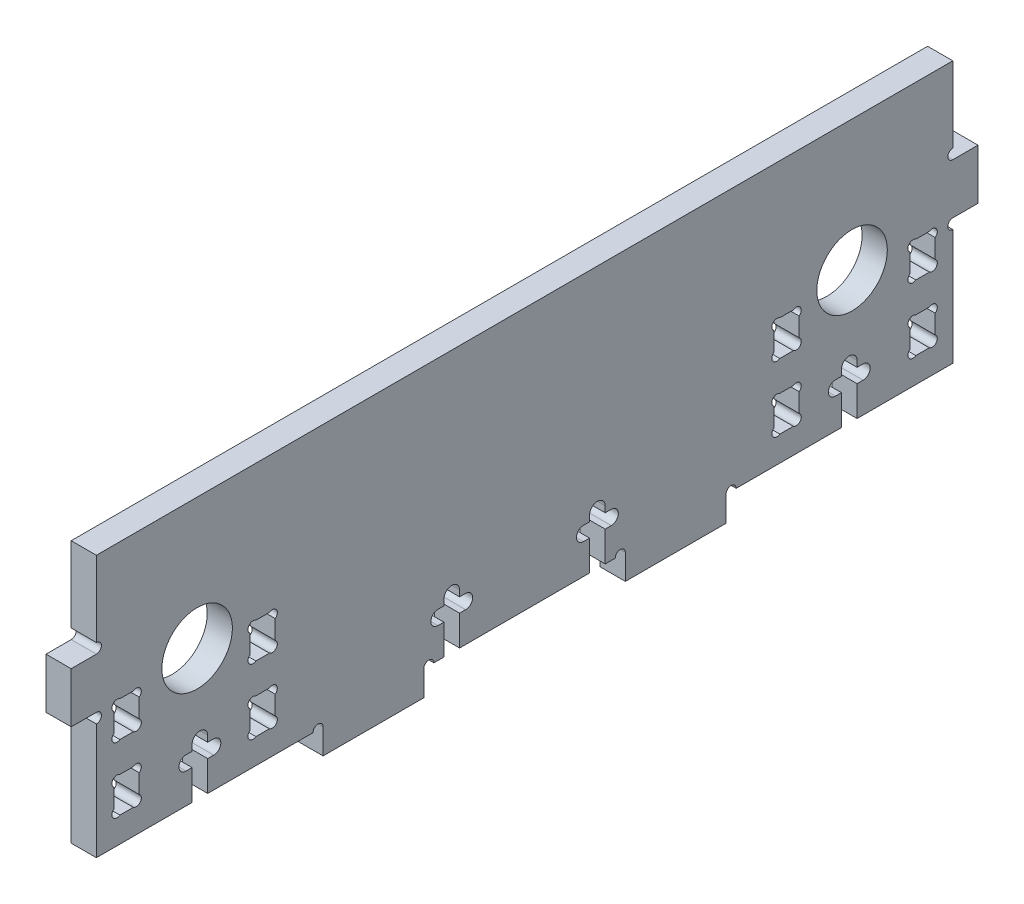
SolidWorks part; units mm, degrees
ref_plane "정면" through (0, 0, 0) normal (0, 0, 1) x (1, 0, 0)
ref_plane "윗면" through (0, 0, 0) normal (0, 1, 0) x (1, 0, 0)
ref_plane "우측면" through (0, 0, 0) normal (1, 0, 0) x (0, 0, -1)
sketch "스케치1" plane through (0, 0, 0) normal (1, 0, 0) x (0, 0, -1)
  line L1 (0, 0) -> (170, 0)
  line L2 (0, 0) -> (0, 52)
  line L3 (0, 52) -> (170, 52)
  line L4 (170, 0) -> (170, 52)
  dimension "D1" = 170
  dimension "D2" = 52
extrude "보스-돌출1" add sketch "스케치1" along normal blind 5
sketch "스케치2" plane through (5, 0, 0) normal (1, 0, 0) x (0, 0, -1)
  line L0 (170, 26) -> (150, 26) construction
  line L1 (170, 0) -> (170, 52) construction
  line L2 (150, 26) -> (20, 26) construction
  line L3 (20, 26) -> (0, 26) construction
  line L4 (0, 52) -> (0, 0) construction
  circle A0 centre (150, 26) radius 7
  circle A1 centre (20, 26) radius 7
  dimension "D2" = 14
  dimension "D1" = 20
extrude "컷-돌출1" cut sketch "스케치2" against normal blind 10
sketch "스케치3" plane through (5, 0, 0) normal (1, 0, 0) x (0, 0, -1)
  line L0 (0, 0) -> (170, 0) construction
  line L1 (45, 0) -> (65, 0)
  line L2 (45, 0) -> (45, -5)
  line L3 (45, -5) -> (65, -5)
  line L4 (65, 0) -> (65, -5)
  line L5 (0, -5) -> (45, -5) construction
  line L6 (65, -5) -> (105, -5) construction
  line L7 (125, 0) -> (105, 0)
  line L8 (125, 0) -> (125, -5)
  line L9 (125, -5) -> (105, -5)
  line L10 (105, 0) -> (105, -5)
  line L11 (125, -5) -> (170, -5) construction
  line L12 (170, -5) -> (170, 0) construction
  line L13 (0, 0) -> (0, -5) construction
  line L14 (0, 0) -> (0, -5) construction
  line L15 (0, -5) -> (45, -5) construction
  dimension "D1" = 45
  dimension "D2" = 20
extrude "보스-돌출2" add sketch "스케치3" against normal blind 5
sketch "스케치6" plane through (5, 0, 0) normal (1, 0, 0) x (0, 0, -1)
  line L0 (151, 0) -> (151, 6)
  line L1 (147.9, 10) -> (151, 10) construction
  line L2 (146.7, 6) -> (146.7, 8.8) construction
  line L3 (151, 6) -> (151, 8.8) construction
  line L4 (147.9, 0) -> (151, 0)
  line L5 (146.7, 8.8) -> (147.9, 8.8)
  line L6 (147.9, 0) -> (147.9, 6)
  line L7 (152.2, 8.8) -> (152.2, 6) construction
  line L8 (147.9, 6) -> (146.7, 6)
  line L9 (147.9, 8.8) -> (147.9, 6) construction
  line L10 (151, 8.8) -> (151, 10)
  line L11 (147.9, 6) -> (151, 6) construction
  line L12 (147.9, 8.8) -> (151, 8.8) construction
  line L13 (151, 8.8) -> (152.2, 8.8)
  line L14 (147.9, 8.8) -> (147.9, 10)
  line L15 (149.45, 10) -> (149.45, 12.1831) construction
  line L16 (152.2, 6) -> (151, 6)
  line L18 (65, 0) -> (105, 0) construction
  line L19 (101, 0) -> (101, 6)
  line L20 (97.9, 10) -> (101, 10) construction
  line L21 (96.7, 6) -> (96.7, 8.8) construction
  line L22 (101, 6) -> (101, 8.8) construction
  line L23 (97.9, 0) -> (101, 0)
  line L24 (96.7, 8.8) -> (97.9, 8.8)
  line L25 (97.9, 0) -> (97.9, 6)
  line L26 (102.2, 8.8) -> (102.2, 6) construction
  line L27 (97.9, 6) -> (96.7, 6)
  line L28 (97.9, 8.8) -> (97.9, 6) construction
  line L29 (101, 8.8) -> (101, 10)
  line L30 (97.9, 6) -> (101, 6) construction
  line L31 (97.9, 8.8) -> (101, 8.8) construction
  line L32 (101, 8.8) -> (102.2, 8.8)
  line L33 (97.9, 8.8) -> (97.9, 10)
  line L34 (99.45, 10) -> (99.45, 12.1831) construction
  line L35 (102.2, 6) -> (101, 6)
  line L37 (105, 0) -> (105, -5) construction
  line L71 (85, 52) -> (85, 0) construction
  line L72 (170, 52) -> (0, 52) construction
  line L89 (70.55, 10) -> (70.55, 12.1831) construction
  line L90 (72.1, 8.8) -> (69, 8.8) construction
  line L91 (72.1, 6) -> (69, 6) construction
  line L92 (72.1, 8.8) -> (72.1, 6) construction
  line L93 (67.8, 8.8) -> (67.8, 6) construction
  line L94 (69, 6) -> (69, 8.8) construction
  line L95 (73.3, 6) -> (73.3, 8.8) construction
  line L96 (72.1, 10) -> (69, 10) construction
  line L97 (20.55, 10) -> (20.55, 12.1831) construction
  line L98 (22.1, 8.8) -> (19, 8.8) construction
  line L99 (22.1, 6) -> (19, 6) construction
  line L100 (22.1, 8.8) -> (22.1, 6) construction
  line L101 (17.8, 8.8) -> (17.8, 6) construction
  line L102 (19, 6) -> (19, 8.8) construction
  line L103 (23.3, 6) -> (23.3, 8.8) construction
  line L104 (22.1, 10) -> (19, 10) construction
  line L123 (67.8, 6) -> (69, 6)
  line L124 (72.1, 8.8) -> (72.1, 10)
  line L125 (69, 8.8) -> (67.8, 8.8)
  line L126 (69, 8.8) -> (69, 10)
  line L127 (72.1, 6) -> (73.3, 6)
  line L128 (72.1, 0) -> (72.1, 6)
  line L129 (73.3, 8.8) -> (72.1, 8.8)
  line L130 (72.1, 0) -> (69, 0)
  line L131 (69, 0) -> (69, 6)
  line L132 (17.8, 6) -> (19, 6)
  line L133 (22.1, 8.8) -> (22.1, 10)
  line L134 (19, 8.8) -> (17.8, 8.8)
  line L135 (19, 8.8) -> (19, 10)
  line L136 (22.1, 6) -> (23.3, 6)
  line L137 (22.1, 0) -> (22.1, 6)
  line L138 (23.3, 8.8) -> (22.1, 8.8)
  line L139 (22.1, 0) -> (19, 0)
  line L140 (19, 0) -> (19, 6)
  arc A0 (151, 10) -> (147.9, 10) centre (149.45, 10) ccw
  arc A1 (146.7, 8.8) -> (146.7, 6) centre (146.7, 7.4) ccw
  arc A2 (152.2, 6) -> (152.2, 8.8) centre (152.2, 7.4) ccw
  arc A3 (101, 10) -> (97.9, 10) centre (99.45, 10) ccw
  arc A4 (96.7, 8.8) -> (96.7, 6) centre (96.7, 7.4) ccw
  arc A5 (102.2, 6) -> (102.2, 8.8) centre (102.2, 7.4) ccw
  arc A18 (67.8, 6) -> (67.8, 8.8) centre (67.8, 7.4) cw
  arc A19 (73.3, 8.8) -> (73.3, 6) centre (73.3, 7.4) cw
  arc A20 (69, 10) -> (72.1, 10) centre (70.55, 10) cw
  arc A21 (17.8, 6) -> (17.8, 8.8) centre (17.8, 7.4) cw
  arc A22 (23.3, 8.8) -> (23.3, 6) centre (23.3, 7.4) cw
  arc A23 (19, 10) -> (22.1, 10) centre (20.55, 10) cw
  dimension "D1" = 3.1
  dimension "D2" = 4
  dimension "D3" = 5.5
  dimension "D4" = 2.8
  dimension "D7" = 3.1
  dimension "D9" = 5.5
  dimension "D10" = 2.8
  dimension "D12" = 50
extrude "컷-돌출2" cut sketch "스케치6" against normal blind 10
sketch "스케치8" plane through (5, 0, 0) normal (1, 0, 0) x (0, 0, -1)
  line L0 (170, 0) -> (170, 52) construction
  line L1 (170, 35) -> (175, 35)
  line L2 (170, 35) -> (170, 25)
  line L3 (170, 25) -> (175, 25)
  line L4 (175, 35) -> (175, 25)
  line L5 (175, 52) -> (175, 35) construction
  line L8 (85, 0) -> (85, 52) construction
  line L9 (72.1, 0) -> (97.9, 0) construction
  line L10 (170, 52) -> (0, 52) construction
  line L11 (-5, 35) -> (-5, 25)
  line L12 (0, 25) -> (-5, 25)
  line L13 (0, 35) -> (0, 25)
  line L14 (0, 35) -> (-5, 35)
  line L15 (151, 0) -> (170, 0) construction
  dimension "D1" = 25
  dimension "D2" = 10
extrude "보스-돌출3" add sketch "스케치8" against normal blind 5
sketch "스케치7" plane through (5, 0, 0) normal (1, 0, 0) x (0, 0, -1)
  line L0 (65, 0) -> (69, 0) construction
  line L1 (22.1, 0) -> (45, 0) construction
  line L2 (101, 0) -> (105, 0) construction
  line L3 (125, 0) -> (147.9, 0) construction
  line L4 (170, 35) -> (170, 52) construction
  line L5 (170, 0) -> (170, 25) construction
  line L6 (0, 52) -> (0, 35) construction
  line L7 (0, 25) -> (0, 0) construction
  circle A0 centre (66, 0) radius 1
  circle A1 centre (44, 0) radius 1
  circle A2 centre (104, 0) radius 1
  circle A3 centre (126, 0) radius 1
  circle A4 centre (170, 36) radius 1
  circle A5 centre (170, 24) radius 1
  circle A6 centre (0, 36) radius 1
  circle A7 centre (0, 24) radius 1
  dimension "D1" = 2
extrude "컷-돌출3" cut sketch "스케치7" against normal blind 10
sketch "스케치10" plane through (0, 0, 0) normal (-1, 0, 0) x (0, 0, 1)
  line L0 (-166.5, 25) -> (-161.5, 18) construction
  line L1 (-166.5, 18) -> (-161.5, 18)
  line L2 (-166.5, 18) -> (-166.5, 25)
  line L3 (-166.5, 25) -> (-161.5, 25)
  line L4 (-161.5, 18) -> (-161.5, 25)
  line L5 (-161.5, 25) -> (-166.5, 18) construction
  line L6 (-85, 52) -> (-85, 0) construction
  line L7 (-139.5, 18) -> (-134.5, 18)
  line L8 (-139.5, 18) -> (-139.5, 25)
  line L9 (-139.5, 25) -> (-134.5, 25)
  line L10 (-134.5, 18) -> (-134.5, 25)
  line L11 (-166.5, 5) -> (-161.5, 5)
  line L12 (-166.5, 5) -> (-166.5, 12)
  line L13 (-166.5, 12) -> (-161.5, 12)
  line L14 (-161.5, 5) -> (-161.5, 12)
  line L15 (-139.5, 12) -> (-134.5, 12)
  line L16 (-139.5, 12) -> (-139.5, 5)
  line L17 (-139.5, 5) -> (-134.5, 5)
  line L18 (-134.5, 12) -> (-134.5, 5)
  line L19 (-170, 52) -> (0, 52) construction
  line L20 (-72.1, 0) -> (-97.9, 0) construction
  line L21 (-8.5, 25) -> (-3.5, 18) construction
  line L22 (-3.5, 25) -> (-8.5, 18) construction
  line L23 (-35.5, 12) -> (-35.5, 5)
  line L24 (-30.5, 5) -> (-35.5, 5)
  line L25 (-30.5, 12) -> (-30.5, 5)
  line L26 (-30.5, 12) -> (-35.5, 12)
  line L27 (-8.5, 5) -> (-8.5, 12)
  line L28 (-3.5, 12) -> (-8.5, 12)
  line L29 (-3.5, 5) -> (-3.5, 12)
  line L30 (-3.5, 5) -> (-8.5, 5)
  line L31 (-35.5, 18) -> (-35.5, 25)
  line L32 (-30.5, 25) -> (-35.5, 25)
  line L33 (-30.5, 18) -> (-30.5, 25)
  line L34 (-30.5, 18) -> (-35.5, 18)
  line L35 (-8.5, 18) -> (-8.5, 25)
  line L36 (-3.5, 25) -> (-8.5, 25)
  line L37 (-3.5, 18) -> (-3.5, 25)
  line L38 (-3.5, 18) -> (-8.5, 18)
extrude "컷-돌출4" cut sketch "스케치10" against normal blind 10
sketch "스케치11" plane through (5, 0, 0) normal (1, 0, 0) x (0, 0, -1)
  line L0 (85, 52) -> (85, 0) construction
  line L1 (170, 52) -> (0, 52) construction
  line L2 (72.1, 0) -> (97.9, 0) construction
  line L3 (161.5, 25) -> (166.5, 18) construction
  line L4 (166.5, 25) -> (161.5, 18) construction
  line L5 (139.5, 18) -> (161.5, 18) construction
  line L6 (161.5, 18) -> (161.5, 12) construction
  line L7 (161.5, 12) -> (139.5, 12) construction
  line L8 (139.5, 12) -> (139.5, 18) construction
  line L9 (150.5, 18) -> (150.5, 12) construction
  line L10 (139.5, 15) -> (161.5, 15) construction
  line L11 (134.5, 25) -> (139.5, 18) construction
  line L12 (139.5, 25) -> (134.5, 18) construction
  line L13 (139.5, 5) -> (134.5, 12) construction
  line L14 (134.5, 5) -> (139.5, 12) construction
  line L15 (166.5, 5) -> (161.5, 12) construction
  line L16 (161.5, 5) -> (166.5, 12) construction
  line L17 (8.5, 5) -> (3.5, 12) construction
  line L18 (3.5, 5) -> (8.5, 12) construction
  line L19 (35.5, 5) -> (30.5, 12) construction
  line L20 (30.5, 5) -> (35.5, 12) construction
  line L21 (30.5, 25) -> (35.5, 18) construction
  line L22 (35.5, 25) -> (30.5, 18) construction
  line L23 (30.5, 15) -> (8.5, 15) construction
  line L24 (19.5, 18) -> (19.5, 12) construction
  line L25 (30.5, 12) -> (30.5, 18) construction
  line L26 (8.5, 12) -> (30.5, 12) construction
  line L27 (8.5, 18) -> (8.5, 12) construction
  line L28 (30.5, 18) -> (8.5, 18) construction
  line L29 (3.5, 25) -> (8.5, 18) construction
  line L30 (8.5, 25) -> (3.5, 18) construction
  circle A0 centre (165.9188, 24.1863) radius 1
  circle A1 centre (162.0812, 24.1863) radius 1
  circle A2 centre (165.9188, 18.8137) radius 1
  circle A3 centre (162.0812, 18.8137) radius 1
  circle A4 centre (138.9188, 18.8137) radius 1
  circle A5 centre (135.0812, 18.8137) radius 1
  circle A6 centre (138.9188, 24.1863) radius 1
  circle A7 centre (135.0812, 24.1863) radius 1
  circle A8 centre (135.0812, 5.8137) radius 1
  circle A9 centre (138.9188, 5.8137) radius 1
  circle A10 centre (135.0812, 11.1863) radius 1
  circle A11 centre (138.9188, 11.1863) radius 1
  circle A12 centre (162.0812, 11.1863) radius 1
  circle A13 centre (165.9188, 11.1863) radius 1
  circle A14 centre (162.0812, 5.8137) radius 1
  circle A15 centre (165.9188, 5.8137) radius 1
  circle A16 centre (4.0812, 5.8137) radius 1
  circle A17 centre (7.9188, 5.8137) radius 1
  circle A18 centre (4.0812, 11.1863) radius 1
  circle A19 centre (7.9188, 11.1863) radius 1
  circle A20 centre (31.0812, 11.1863) radius 1
  circle A21 centre (34.9188, 11.1863) radius 1
  circle A22 centre (31.0812, 5.8137) radius 1
  circle A23 centre (34.9188, 5.8137) radius 1
  circle A24 centre (34.9188, 24.1863) radius 1
  circle A25 centre (31.0812, 24.1863) radius 1
  circle A26 centre (34.9188, 18.8137) radius 1
  circle A27 centre (31.0812, 18.8137) radius 1
  circle A28 centre (7.9188, 18.8137) radius 1
  circle A29 centre (4.0812, 18.8137) radius 1
  circle A30 centre (7.9188, 24.1863) radius 1
  circle A31 centre (4.0812, 24.1863) radius 1
  dimension "D1" = 2
extrude "컷-돌출5" cut sketch "스케치11" against normal blind 10
